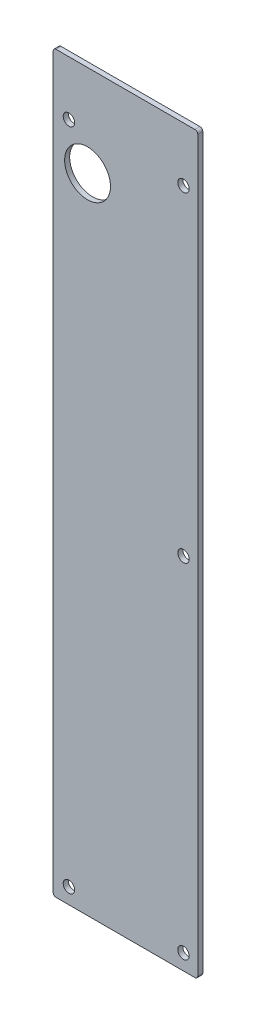
SolidWorks part; units mm, degrees
material "Acrylic (Medium-high impact)"
ref_plane "Front Plane" through (0, 0, 0) normal (0, 0, 1) x (1, 0, 0)
ref_plane "Top Plane" through (0, 0, 0) normal (0, 1, 0) x (1, 0, 0)
ref_plane "Right Plane" through (0, 0, 0) normal (1, 0, 0) x (0, 0, -1)
sketch "Sketch1" plane through (0, 0, 0) normal (0, 0, 1) x (1, 0, 0)
  line L1 (0, 0) -> (160.3375, 0)
  line L2 (0, 0) -> (0, 814.3875)
  line L3 (0, 814.3875) -> (160.3375, 814.3875)
  line L4 (160.3375, 0) -> (160.3375, 814.3875)
  dimension "D1" = 160.3375
  dimension "D2" = 814.3875
extrude "Boss-Extrude1" add sketch "Sketch1" along normal blind 5.588
fillet "Fillet1" radius 3.175 4 edges at (0, 0, 2.794) (160.3375, 0, 2.794) (0, 814.3875, 2.794) (160.3375, 814.3875, 2.794)
sketch "Sketch2" plane through (0, 0, 5.588) normal (0, 0, 1) x (1, 0, 0)
  line L0 (0, 811.2125) -> (0, 3.175) construction
  line L1 (157.1625, 814.3875) -> (3.175, 814.3875) construction
  line L2 (17.4625, 754.0625) -> (144.4625, 754.0625) construction
  line L3 (144.4625, 754.0625) -> (144.4625, 17.4625) construction
  line L4 (144.4625, 17.4625) -> (17.4625, 17.4625) construction
  circle A0 centre (17.4625, 754.0625) radius 6.35
  circle A1 centre (144.4625, 754.0625) radius 6.35
  circle A2 centre (17.4625, 17.4625) radius 6.35
  circle A3 centre (144.4625, 17.4625) radius 6.35
  circle A4 centre (144.4625, 398.4625) radius 6.35
  dimension "D1" = 12.7
  dimension "D2" = 12.7
  dimension "D8" = 12.7
  dimension ".5" = 12.7
  dimension "D10" = 12.7
  dimension "D3" = 17.4625
  dimension "D4" = 60.325
  dimension "D5" = 127
  dimension "D6" = 736.6
  dimension "D7" = 127
  dimension "D11" = 355.6
extrude "Cut-Extrude1" cut sketch "Sketch2" against normal blind 6.35
sketch "Sketch3" plane through (0, 0, 5.588) normal (0, 0, 1) x (1, 0, 0)
  line L1 (157.1625, 814.3875) -> (3.175, 814.3875) construction
  line L2 (0, 811.2125) -> (0, 3.175) construction
  circle A0 centre (38.1, 712.7875) radius 25.4
  dimension "D1" = 50.8
  dimension "D2" = 38.1
  dimension "D3" = 101.6
extrude "Cut-Extrude2" cut sketch "Sketch3" against normal through all
